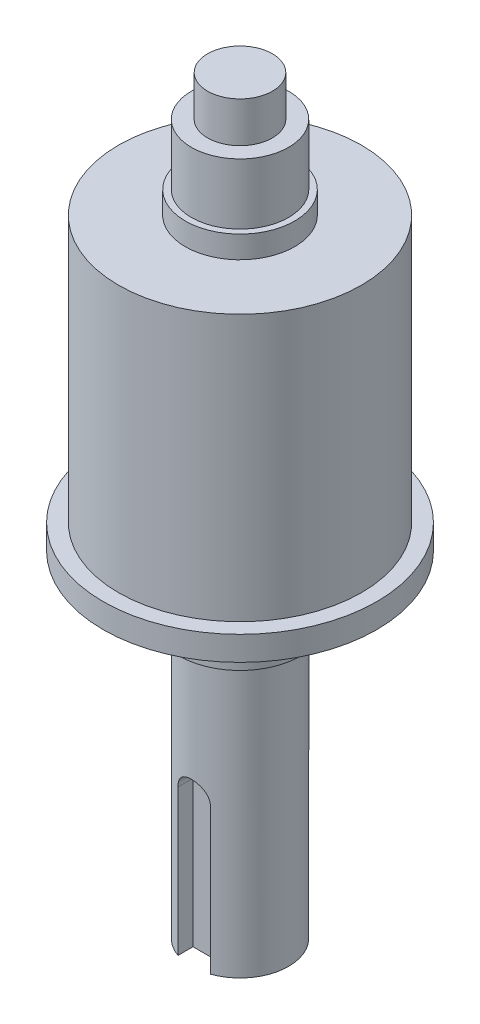
SolidWorks part; units mm, degrees
material "AISI 1035 Steel (SS)"
ref_plane "Front Plane" through (0, 0, 0) normal (0, 0, 1) x (1, 0, 0)
ref_plane "Top Plane" through (0, 0, 0) normal (0, 1, 0) x (1, 0, 0)
ref_plane "Right Plane" through (0, 0, 0) normal (1, 0, 0) x (0, 0, -1)
sketch "Sketch2" plane through (0, 0, 0) normal (0, 0, 1) x (1, 0, 0)
  line L0 (0, 40.0334) -> (0, -27.2464) construction
  line L11 (0, 0) -> (-4, 0)
  line L12 (-4, 0) -> (-4, -5)
  line L13 (-4, -5) -> (-6, -5)
  line L14 (-6, -5) -> (-6, -12.5)
  line L15 (-6, -12.5) -> (-6.75, -12.5)
  line L16 (-6.75, -12.5) -> (-6.75, -15.25)
  line L17 (-6.75, -15.25) -> (-14.9815, -15.25)
  line L18 (-14.9815, -15.25) -> (-14.9815, -48.11)
  line L26 (0, -92.535) -> (0, 0)
  line L28 (-16.8815, -51.11) -> (-16.8815, -48.11)
  line L29 (-16.8815, -48.11) -> (-14.9815, -48.11)
  line L30 (-16.8815, -51.11) -> (-8.25, -51.11)
  line L31 (-8.25, -51.11) -> (-8.25, -53.61)
  line L32 (-14.9815, -48.11) -> (-14.9815, -51.11) construction
  line L33 (-8.25, -53.61) -> (-7.5, -53.61)
  line L34 (-7.5, -53.61) -> (-7.5, -58.61)
  line L35 (-7.5, -58.61) -> (-6, -58.61)
  line L36 (-6, -58.61) -> (-6, -92.535)
  line L37 (-6, -92.535) -> (0, -92.535)
  dimension "D1" = 4
  dimension "D2" = 5
  dimension "D3" = 6
  dimension "D4" = 7.5
  dimension "D5" = 6.75
  dimension "D6" = 2.75
  dimension "D7" = 14.9815
  dimension "D8" = 32.86
  dimension "D10" = 3
  dimension "D11" = 8.25
  dimension "D12" = 2.5
  dimension "D13" = 7.5
  dimension "D14" = 5
  dimension "D15" = 6
  dimension "D16" = 33.925
  dimension "D9" = 1.9
revolve "Revolve1" add sketch "Sketch2" angle 360 about L0
sketch "Sketch3" plane through (0, -92.535, 0) normal (0, -1, 0) x (1, 0, 0)
  line L4 (-2, 5.6569) -> (-2, 7.8) construction
  line L5 (-2, 7.8) -> (2, 7.8) construction
  line L6 (2, 7.8) -> (2, 5.6569) construction
  line L7 (0, -6) -> (12.9978, -6) construction
  line L8 (-2, 5.6569) -> (-2, 3.8)
  line L9 (-2, 3.8) -> (2, 3.8)
  line L10 (2, 3.8) -> (2, 5.6569)
  circle A1 centre (0, 0) radius 6
  arc A2 (2, 5.6569) -> (-2, 5.6569) centre (0, 0) ccw
  point P2 (0, 7.8)
  dimension "D2" = 4
  dimension "D3" = 13.8
  dimension "D4" = 4
extrude "Cut-Extrude1" cut sketch "Sketch3" against normal blind 15
sketch "Sketch4" plane through (0, 0, 3.8) normal (0, 0, 1) x (1, 0, 0)
  line L0 (-2, -77.535) -> (-2, -74.535)
  line L1 (2, -74.535) -> (2, -77.535)
  line L2 (-4.5886, -72.535) -> (3.957, -72.535) construction
  line L3 (-2, -92.535) -> (2, -92.535) construction
  line L4 (-2, -77.535) -> (-2, -92.535)
  line L5 (-2, -92.535) -> (2, -92.535)
  line L6 (2, -92.535) -> (2, -77.535)
  arc A0 (-2, -74.535) -> (2, -74.535) centre (0, -74.535) cw
  dimension "D1" = 20
extrude "Cut-Extrude2" cut sketch "Sketch4" along normal through all
equation "\"Stator_OD\"= 60'No Tolerance given"
equation "\"A\"=35.81 'taken off spec sheet for 06808 (A)"
equation "\"Rotor_ID\"= 30'No Tolerance Given"
equation "\"back_bearing_Thickness\"= 5'-0.12"
equation "\"back_bearing_OD\"= 24'-0.009 https://www.mcmaster.com/5972K155/"
equation "\"Stator_Gap\"= 0.0375'+- 0.0125 (From 1.3.3.1 Kollmorgen manual)"
equation "\"Back_mount_hole\"= 1.75'To be tapped to M2 (USE LOCKTITE)"
equation "\"facePlate_Mount_Hole\"= 2.75'To be tapped to M3"
equation "\"final_shaftD\"= 12'To fit in harmonic"
equation "\"back_bearing_ID\"= 15'"
equation "\"rotor_shaftD\"= \"Rotor_ID\" - (\"rotor-shaft_gap\")*2'"
equation "\"back_bearing_IDOD\"= 16.5'measured off CAD, actually 16.75, but rounded down to nicer number"
equation "\"final_shaftL\"= 5.25+3+\"sheet_thick\"+\"connector_thick\"-3+\"harmon_coupleL\"+0.5-\"shaft_Ladjust\"'length to make everything nice and aligned"
equation "\"D1@Sketch2\"=4"
equation "\"D3@Sketch2\"=\"front_bearing_ID\"/2"
equation "\"D4@Sketch2\" = \"front_bearing_Thickness\" + 2.5"
equation "\"D5@Sketch2\"=\"front_bearing_IDOD\" / 2"
equation "\"D8@Sketch2\"=\"rotor_height\""
equation "\"front_bearing_ID\"= 12'https://www.mcmaster.com/5972K154/"
equation "\"front_bearing_OD\"= 21'-0.009"
equation "\"front_bearing_IDOD\"= 13.5'Measured off CAD. Actually 13.75, but rounded down"
equation "\"front_bearing_Thickness\"= 5'-0.12"
equation "\"rotor_thickness\"= 2.4'measured off CAD"
equation "\"rotor_height\"= 32.86'+-0.075 taken off spec sheet for 06826 (C)"
equation "\"D11@Sketch2\"=\"back_bearing_IDOD\"/2"
equation "\"D13@Sketch2\"=\"back_bearing_ID\"/2"
equation "\"D14@Sketch2\"=\"back_bearing_Thickness\""
equation "\"D15@Sketch2\"=\"final_shaftD\"/2"
equation "\"D16@Sketch2\"=\"final_shaftL\""
equation "\"D9@Sketch2\"=\"rotor_thickness\"-0.5"
equation "\"rotor-shaft_gap\" = 0.0185 '+-0.0065 (from manual)"
equation "\"D7@Sketch2\"=\"Rotor_ID\"/2-\"rotor-shaft_gap\""
equation "\"B\"= 26.3'+-0.35 taken off spec sheet for 06826"
equation "\"key_L\"= 20'-0.2 https://www.mcmaster.com/2977N19/"
equation "\"key_H\"= 4'-0.03"
equation "\"key_W\"= 4'-0.03"
equation "\"harmon_keyH\"= 13.8'+0.1 from drawing"
equation "\"harmon_coupleL\"= 21.5' taken from drawing https://www.harmonicdrive.net/_hd/content/caddownloads/dxf/csg-2uh-lw_gearheads/csg-20-100-2uh-lw.pdf"
equation "\"D2@Sketch3\"=\"key_W\""
equation "\"D3@Sketch3\"=\"harmon_keyH\""
equation "\"D4@Sketch3\"=\"key_H\""
equation "\"D1@Cut-Extrude1\"=\"key_L\"-5"
equation "\"D1@Sketch4\"=\"key_L\""
equation "\"harmon_diam\"= 93' from drawing"
equation "\"harmon_BCD\"= 82' from drawing"
equation "\"harmon_holeD1\"= 5.5' from drawing"
equation "\"harmon_holeD2\"= 5' from drawing"
equation "\"harmon_holeAng\"= 22.5' from drawing"
equation "\"sheet_thick\"= 1/8*25.4 'random, replace w actual sheet thickness when u feel like :)"
equation "\"nut-thickness\"= 5 'idk measure the ones in the shop and adjust"
equation "\"connector_thick\"= 10' random for now"
equation "\"shaft_Ladjust\"= 6.5' sorry. It's silly, but it works."
